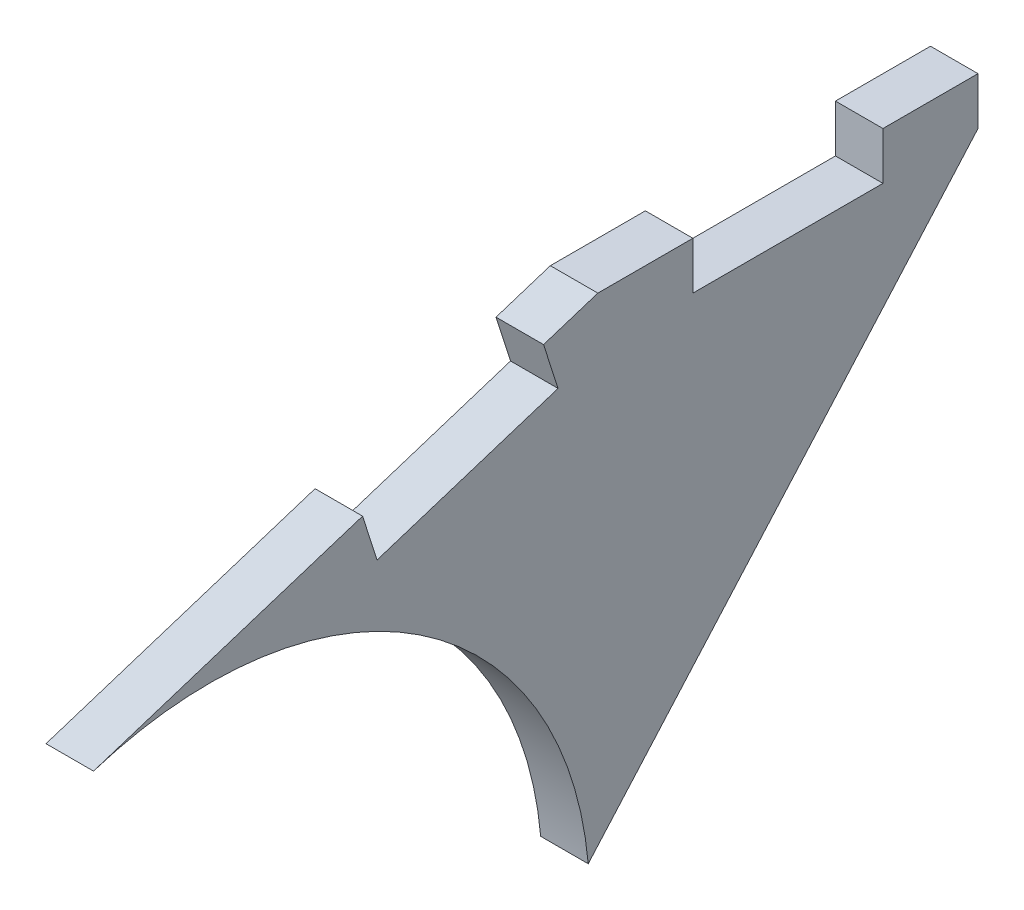
SolidWorks part; units mm, degrees
material "AISI 4130 Steel, annealed at 865C"
ref_plane "X-Y Datum" through (0, 0, 0) normal (0, 0, 1) x (1, 0, 0)
ref_plane "X-Z Datum" through (0, 0, 0) normal (0, 1, 0) x (1, 0, 0)
ref_plane "Y-Z Datum" through (0, 0, 0) normal (1, 0, 0) x (0, 0, -1)
sketch "Sketch1" plane through (0, 0, 0) normal (1, 0, 0) x (0, 0, -1)
  line L1 (-6.398, -0.7518) -> (-6.398, -2.3393)
  line L3 (-19.098, -0.7518) -> (-20.912, -1.3337)
  line L4 (-6.398, -2.3393) -> (-19.4195, -17.1022)
  line L7 (-6.398, -0.7518) -> (-9.573, -0.7518)
  line L8 (-9.573, -0.7518) -> (-9.573, -2.3393)
  line L9 (-9.573, -2.3393) -> (-15.923, -2.3393)
  line L10 (-15.923, -2.3393) -> (-15.923, -0.7518)
  line L12 (-15.923, -0.7518) -> (-19.098, -0.7518)
  line L16 (-6.398, -2.3393) -> (-6.398, -0.7518) construction
  line L17 (-26.9584, -3.2734) -> (-35.9469, -6.1569)
  line L18 (-20.912, -1.3337) -> (-26.9584, -3.2734) construction
  line L19 (-20.912, -1.3337) -> (-20.427, -2.8454)
  line L20 (-20.427, -2.8454) -> (-26.4735, -4.7851)
  line L21 (-26.4735, -4.7851) -> (-26.9584, -3.2734)
  line L24 (-9.573, -2.3393) -> (-15.923, -2.3393) construction
  arc A0 (-19.4195, -17.1022) -> (-35.9469, -6.1569) centre (-32.0675, -18.2499) ccw
  dimension "D1" = 25.4
  dimension "D2" = 6.35
  dimension "D3" = 1.5875
  dimension "D4" = 3.175
  dimension "D5" = 1.5875
  dimension "D6" = 6.35
  dimension "D7" = 1.905
  dimension "D8" = 19.685
  dimension "D9" = 3.175
extrude "Boss-Extrude1" add sketch "Sketch1" along normal blind 1.5875
